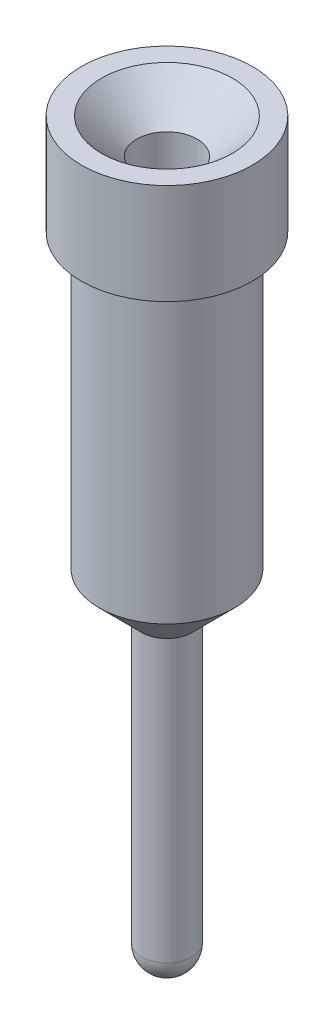
SolidWorks part; units mm, degrees
material "Beryllium Copper, UNS C17300"
ref_plane "Front Plane" through (0, 0, 0) normal (0, 0, 1) x (1, 0, 0)
ref_plane "Top Plane" through (0, 0, 0) normal (0, 1, 0) x (1, 0, 0)
ref_plane "Right Plane" through (0, 0, 0) normal (1, 0, 0) x (0, 0, -1)
sketch "Sketch1" plane through (0, 0, 0) normal (0, 0, 1) x (1, 0, 0)
  line L0 (-0.85, 0) -> (-0.65, 0)
  line L1 (-0.65, 0) -> (-0.3, -0.35)
  line L2 (-0.3, -0.35) -> (-0.3, -3.7)
  line L3 (-0.3, -3.7) -> (0, -4)
  line L4 (0, -4) -> (0, -7.37)
  line L5 (-0.85, 0) -> (-0.85, -1)
  line L6 (-0.85, -1) -> (-0.675, -1)
  line L7 (-0.675, -1) -> (-0.675, -3.9)
  line L8 (-0.675, -3.9) -> (-0.25, -4.325)
  line L9 (-0.25, -4.325) -> (-0.25, -7.12)
  line L10 (0, 0) -> (0, -50000) construction
  arc A0 (-0.25, -7.12) -> (0, -7.37) centre (0, -7.12) ccw
  dimension "D1" = 0.35
  dimension "D2" = 0.35
  dimension "D3" = 45
  dimension "D4" = 0.5
  dimension "D5" = 1.7
  dimension "D6" = 7.12
  dimension "D7" = 0.6
  dimension "D8" = 1.35
  dimension "D9" = 1
  dimension "D10" = 3.9
  dimension "D11" = 3.7
  dimension "D12" = 0.25
revolve "Revolve1" add sketch "Sketch1" angle 360 about L10
